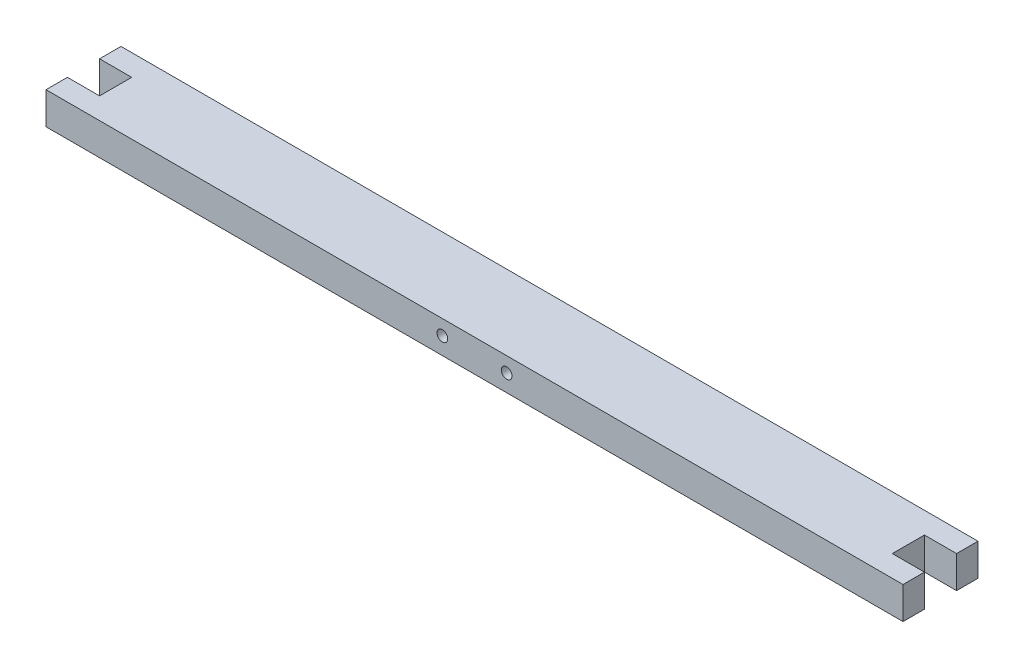
SolidWorks part; units mm, degrees
ref_plane "前视基准面" through (0, 0, 0) normal (0, 0, 1) x (1, 0, 0)
ref_plane "上视基准面" through (0, 0, 0) normal (0, 1, 0) x (1, 0, 0)
ref_plane "右视基准面" through (0, 0, 0) normal (1, 0, 0) x (0, 0, -1)
sketch "草图3" plane through (0, 0, 0) normal (0, 1, 0) x (1, 0, 0)
  line L0 (0, 0) -> (400, 0)
  line L1 (0, 0) -> (0, 10)
  line L2 (400, 0) -> (400, 10)
  line L3 (0, 35) -> (400, 35)
  line L4 (0, 10) -> (15, 10)
  line L6 (15, 10) -> (15, 25)
  line L7 (0, 25) -> (15, 25)
  line L8 (0, 25) -> (0, 35)
  line L10 (400, 10) -> (385, 10)
  line L11 (400, 25) -> (385, 25)
  line L12 (385, 10) -> (385, 25)
  line L13 (400, 25) -> (400, 35)
  dimension "D1" = 10
  dimension "D2" = 10
  dimension "D3" = 10
  dimension "D4" = 15
  dimension "D5" = 10
  dimension "D6" = 15
  dimension "D7" = 400
  dimension "D8" = 15
  dimension "D9" = 15
  dimension "D10" = 15
extrude "凸台-拉伸1" add sketch "草图3" along normal blind 15 contours L3 L13 L11 L12 L10 L2 L0 L1 L4 L6 L7 L8
sketch "草图4" plane through (0, 0, 0) normal (0, 0, 1) x (1, 0, 0)
  line L0 (0, 15) -> (400, 15) construction
  circle A0 centre (185, 8) radius 2.5
  circle A1 centre (215, 8) radius 2.5
  point P6 (200, 15)
  dimension "D1" = 7
  dimension "D2" = 7
  dimension "D3" = 15
  dimension "D4" = 30
extrude "切除-拉伸1" cut sketch "草图4" against normal blind 35
